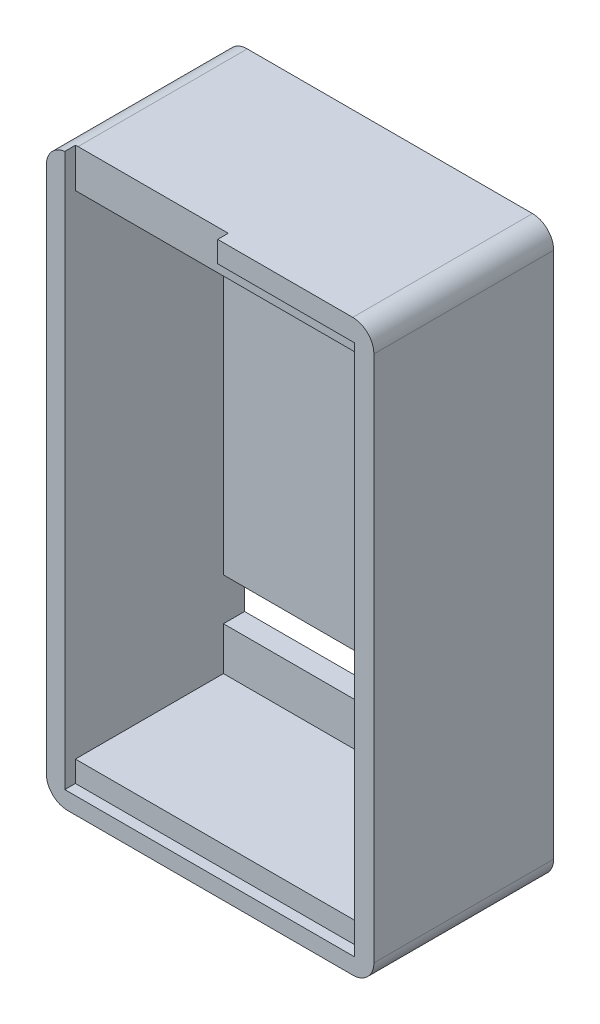
SolidWorks part; units mm, degrees
ref_plane "Front Plane" through (0, 0, 0) normal (0, 0, 1) x (1, 0, 0)
ref_plane "Top Plane" through (0, 0, 0) normal (0, 1, 0) x (1, 0, 0)
ref_plane "Right Plane" through (0, 0, 0) normal (1, 0, 0) x (0, 0, -1)
sketch "草图3" plane through (0, 0, 0) normal (0, 0, 1) x (1, 0, 0)
  line L6 (36.6667, -24.8877) -> (67.6414, -24.8877)
  line L7 (67.6414, -24.8877) -> (67.6414, -78.7564)
  line L10 (67.6414, -78.7564) -> (36.6667, -78.7564)
  line L11 (36.6667, -78.7564) -> (36.6667, -24.8877)
  line L12 (39.654, -26.8877) -> (64.6541, -26.8877) construction
  line L13 (65.6414, -27.875) -> (65.6414, -75.875) construction
  line L14 (38.6667, -72.8424) -> (38.6667, -48.9006) construction
  line L16 (38.6667, -29.6037) -> (38.6667, -27.875) construction
  line L17 (38.6667, -48.9006) -> (38.6667, -29.6496) construction
  line L18 (38.6667, -75.875) -> (38.6667, -72.8424) construction
  line L19 (58.3263, -76.8631) -> (39.654, -76.8624) construction
  line L20 (58.3263, -75.262) -> (58.3263, -76.8631) construction
  line L21 (62.5301, -75.2493) -> (58.339, -75.2493) construction
  line L22 (62.5428, -76.8751) -> (62.5428, -75.262) construction
  line L23 (64.6541, -76.8624) -> (62.5428, -76.9001) construction
  line L24 (38.6667, -29.6037) -> (38.6667, -27.875)
  line L25 (38.6667, -48.9006) -> (38.6667, -29.6496)
  line L26 (38.6667, -72.8424) -> (38.6667, -48.9006)
  line L27 (38.6667, -75.875) -> (38.6667, -72.8424)
  line L28 (58.3263, -76.8631) -> (39.654, -76.8624)
  line L29 (58.3263, -75.262) -> (58.3263, -76.8631)
  line L30 (62.5301, -75.2493) -> (58.339, -75.2493)
  line L31 (62.5428, -76.8751) -> (62.5428, -75.262)
  line L32 (64.6541, -76.8624) -> (62.5428, -76.9001)
  line L33 (65.6414, -27.875) -> (65.6414, -75.875)
  line L34 (39.654, -26.8877) -> (64.6541, -26.8877)
  arc A0 (38.6667, -75.875) -> (39.654, -76.8624) centre (39.654, -75.875) ccw construction
  arc A1 (64.6541, -76.8624) -> (65.6414, -75.875) centre (64.6541, -75.875) ccw construction
  arc A2 (65.6414, -27.875) -> (64.6541, -26.8877) centre (64.6541, -27.875) ccw construction
  arc A3 (39.654, -26.8877) -> (38.6667, -27.875) centre (39.654, -27.875) ccw construction
  arc A4 (38.6667, -75.875) -> (39.654, -76.8624) centre (39.654, -75.875) ccw
  arc A5 (64.6541, -76.8624) -> (65.6414, -75.875) centre (64.6541, -75.875) ccw
  arc A6 (65.6414, -27.875) -> (64.6541, -26.8877) centre (64.6541, -27.875) ccw
  arc A7 (39.654, -26.8877) -> (38.6667, -27.875) centre (39.654, -27.875) ccw
  dimension "D1" = 2
  dimension "D2" = 2
  dimension "D3" = 2
extrude "凸台-拉伸1" add sketch "草图3" along normal blind 17
sketch "草图5" plane through (0, 0, 17) normal (0, 0, 1) x (1, 0, 0)
  line L1 (38.4139, -26.6161) -> (65.7955, -26.6161)
  line L2 (65.7955, -26.6161) -> (65.7955, -77.1753)
  line L3 (65.7955, -77.1753) -> (38.4139, -77.1753)
  line L4 (38.4139, -77.1753) -> (38.4139, -26.6161)
extrude "切除-拉伸1" cut sketch "草图5" against normal blind 15
sketch "草图6" plane through (0, 0, 2) normal (0, 0, 1) x (1, 0, 0)
  line L0 (38.4139, -26.6161) -> (38.4139, -77.1753) construction
  line L1 (38.4139, -26.6161) -> (65.7955, -26.6161)
  line L2 (38.4139, -26.6161) -> (38.4139, -28.6161)
  line L3 (38.4139, -28.6161) -> (65.7955, -28.6161)
  line L4 (65.7955, -26.6161) -> (65.7955, -28.6161)
  line L5 (65.7955, -26.6161) -> (38.4139, -26.6161) construction
  line L6 (65.7955, -77.1753) -> (65.7955, -26.6161) construction
  line L7 (65.7955, -77.1753) -> (65.7955, -26.6161) construction
  line L8 (38.4139, -77.1753) -> (65.7955, -77.1753)
  line L9 (38.4139, -77.1753) -> (38.4139, -75.1753)
  line L10 (38.4139, -75.1753) -> (65.7955, -75.1753)
  line L11 (65.7955, -77.1753) -> (65.7955, -75.1753)
extrude "凸台-拉伸2" add sketch "草图6" along normal blind 14
sketch "草图9" plane through (0, 0, 17) normal (0, 0, 1) x (1, 0, 0)
  line L0 (36.6667, -24.8877) -> (67.6414, -24.8877) construction
  line L1 (38.4139, -26.6161) -> (65.8048, -26.6161)
  line L2 (38.4139, -26.6161) -> (38.4139, -24.8877)
  line L3 (38.4139, -24.8877) -> (65.8048, -24.8877)
  line L4 (65.8048, -26.6161) -> (65.8048, -24.8877)
extrude "切除-拉伸3" cut sketch "草图9" against normal blind 1
sketch "草图10" plane through (0, 0, 16) normal (0, 0, 1) x (1, 0, 0)
  line L0 (39.654, -26.8877) -> (64.6541, -26.8877) construction
  line L1 (65.8048, -24.8877) -> (52.8696, -24.8877)
  line L2 (65.8048, -24.8877) -> (65.8048, -26.8877)
  line L3 (65.8048, -26.8877) -> (52.8696, -26.8877)
  line L4 (52.8696, -24.8877) -> (52.8696, -26.8877)
extrude "凸台-拉伸4" add sketch "草图10" along normal up to surface (1 mm away) up to face at (54.8645, -46.4646, 17)
fillet "圆角1" radius 2 4 edges at (67.6414, -78.7564, 8.5) (36.6667, -78.7564, 8.5) (36.6667, -24.8877, 8.5) (67.6414, -24.8877, 8.5)
sketch "草图11" plane through (0, 0, 2) normal (0, 0, 1) x (1, 0, 0)
  line L0 (38.4139, -28.6161) -> (38.4139, -75.1753) construction
  line L1 (38.4139, -32.8271) -> (65.7955, -32.8271)
  line L2 (38.4139, -32.8271) -> (38.4139, -36.8271)
  line L3 (38.4139, -36.8271) -> (65.7955, -36.8271)
  line L4 (65.7955, -32.8271) -> (65.7955, -36.8271)
  line L5 (65.7955, -77.1753) -> (65.7955, -26.8877) construction
  line L7 (38.4139, -67.0903) -> (65.7955, -67.0903)
  line L8 (38.4139, -67.0903) -> (38.4139, -71.0903)
  line L9 (38.4139, -71.0903) -> (65.7955, -71.0903)
  line L10 (65.7955, -67.0903) -> (65.7955, -71.0903)
extrude "切除-拉伸4" cut sketch "草图11" against normal blind 10
